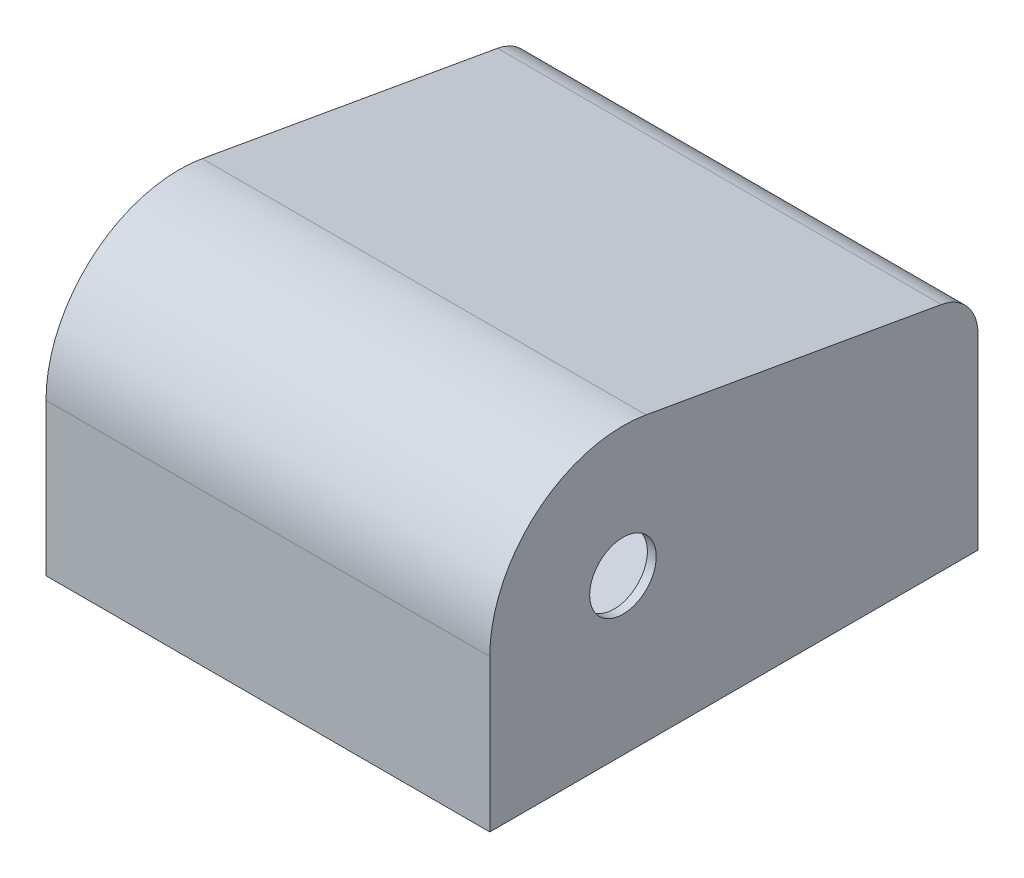
SolidWorks part; units mm, degrees
ref_plane "Спереди" through (0, 0, 0) normal (0, 0, 1) x (1, 0, 0)
ref_plane "Сверху" through (0, 0, 0) normal (0, 1, 0) x (1, 0, 0)
ref_plane "Справа" through (0, 0, 0) normal (1, 0, 0) x (0, 0, -1)
sketch "Профіль корпуса" plane through (0, 0, 0) normal (1, 0, 0) x (0, 0, -1)
  line L1 (0, 0) -> (1100, 0)
  line L2 (0, 0) -> (0, 700)
  line L3 (0, 700) -> (1100, 700)
  line L4 (1100, 0) -> (1100, 700)
  dimension "Довжина" = 1100
  dimension "Висота" = 700
extrude "Корпус" add sketch "Профіль корпуса" along normal blind 1000
draft "Ухил" type of draft neutral plane draft angle 10 faces to draft 1 face at (500, 700, -550) neutral plane through (1000, 0, 0) neutral plane normal (0, 0, 1) reverse direction yes parameters "D1"=10
fillet "Скруглення1" radius 300 1 edges at (500, 700, 0)
fillet "Скруглення2" radius 100 1 edges at (500, 506.0403, -1100)
shell "Оболонка" thickness 20
sketch "Профіль отвору" plane through (0, 0, 0) normal (1, 0, 0) x (0, 0, -1)
  line L2 (0, 0) -> (1100, 0) construction
  line L3 (0, 342.4739) -> (0, 0) construction
  circle A2 centre (300, 350) radius 75
  dimension "Діаметр" = 150
  dimension "Висота осі" = 350
  dimension "Координата осі" = 300
extrude "Отвір" cut sketch "Профіль отвору" along normal through all
equation "\"Висота осі@Профіль отвору\" = 350"
equation "\"Координата осі@Профіль отвору\" = 300"
equation "\"Довжина@Профіль корпуса\"= 1100"
